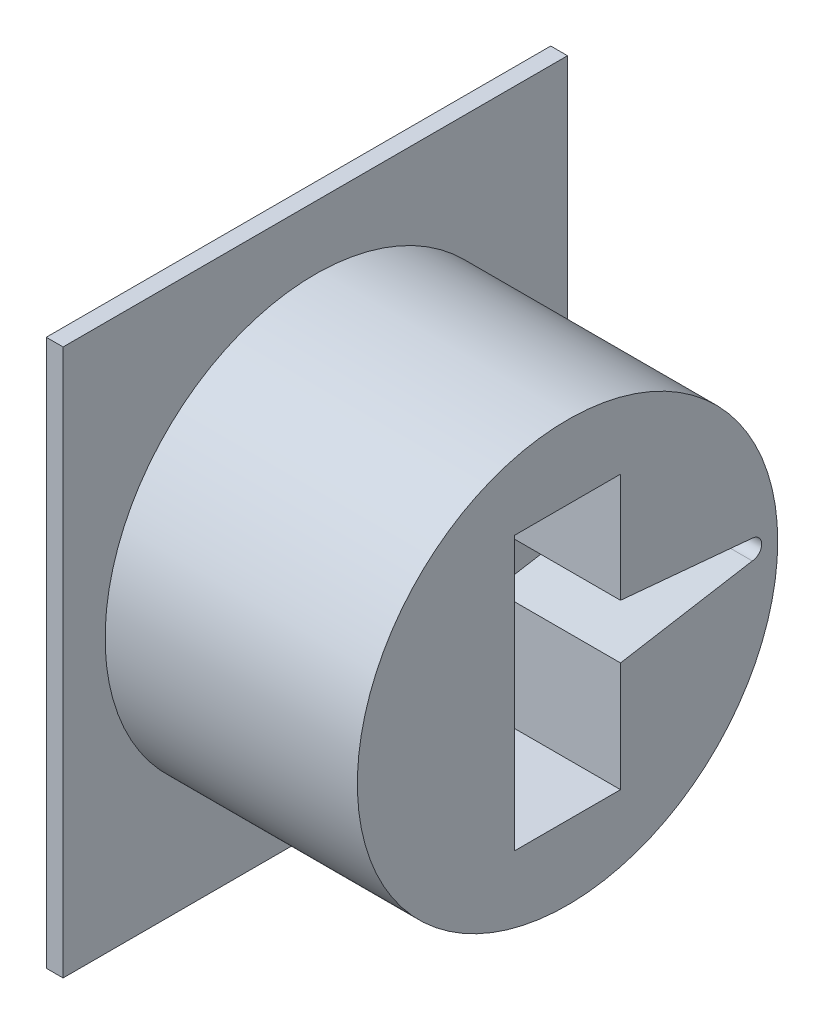
SolidWorks part; units mm, degrees
ref_plane "Front Plane" through (0, 0, 0) normal (0, 0, 1) x (1, 0, 0)
ref_plane "Top Plane" through (0, 0, 0) normal (0, 1, 0) x (1, 0, 0)
ref_plane "Right Plane" through (0, 0, 0) normal (1, 0, 0) x (0, 0, -1)
sketch "Sketch3" plane through (0, 0, 0) normal (1, 0, 0) x (0, 0, -1)
  circle A0 centre (0, 0) radius 25
  dimension "D1" = 50
extrude "Boss-Extrude2" add sketch "Sketch3" along normal blind 30
sketch "Sketch4" plane through (30, 0, 0) normal (1, 0, 0) x (0, 0, -1)
  line L0 (0, 22.3863) -> (0, 16.25) construction
  line L1 (25, 0) -> (6.3, 0) construction
  line L2 (6.3, 3.2528) -> (22.0233, 1.8126)
  line L3 (-6.3, -16.25) -> (6.3, -16.25)
  line L4 (-6.3, -16.25) -> (-6.3, 16.25)
  line L5 (-6.3, 16.25) -> (6.3, 16.25)
  line L6 (6.3, -16.25) -> (6.3, -3.1964)
  line L7 (6.3, 3.2528) -> (6.3, 16.25)
  line L9 (6.3, -3.1964) -> (21.9754, -0.5297)
  line L10 (0, -16.25) -> (0, -25) construction
  line L12 (-6.3, 0) -> (-25, 0) construction
  circle A0 centre (0, 0) radius 25 construction
  arc A2 (22.0233, 1.8126) -> (21.9754, -0.5297) centre (21.9161, 0.6431) cw
  point P7 (0, 0)
  dimension "D4" = 1.1743
  dimension "D1" = 32.5
  dimension "D2" = 12.6
  dimension "D3" = 15.9006
  dimension "D5" = 15.7233
extrude "Cut-Extrude1" cut sketch "Sketch4" against normal blind 15
sketch "Sketch6" plane through (0, 0, 0) normal (-1, 0, 0) x (0, 0, 1)
  line L1 (-30, -32.5) -> (30, -32.5)
  line L2 (-30, -32.5) -> (-30, 32.5)
  line L3 (-30, 32.5) -> (30, 32.5)
  line L4 (30, -32.5) -> (30, 32.5)
  line L5 (-30, -32.5) -> (30, 32.5) construction
  line L6 (-30, 32.5) -> (30, -32.5) construction
extrude "Boss-Extrude3" add sketch "Sketch6" along normal blind 2
